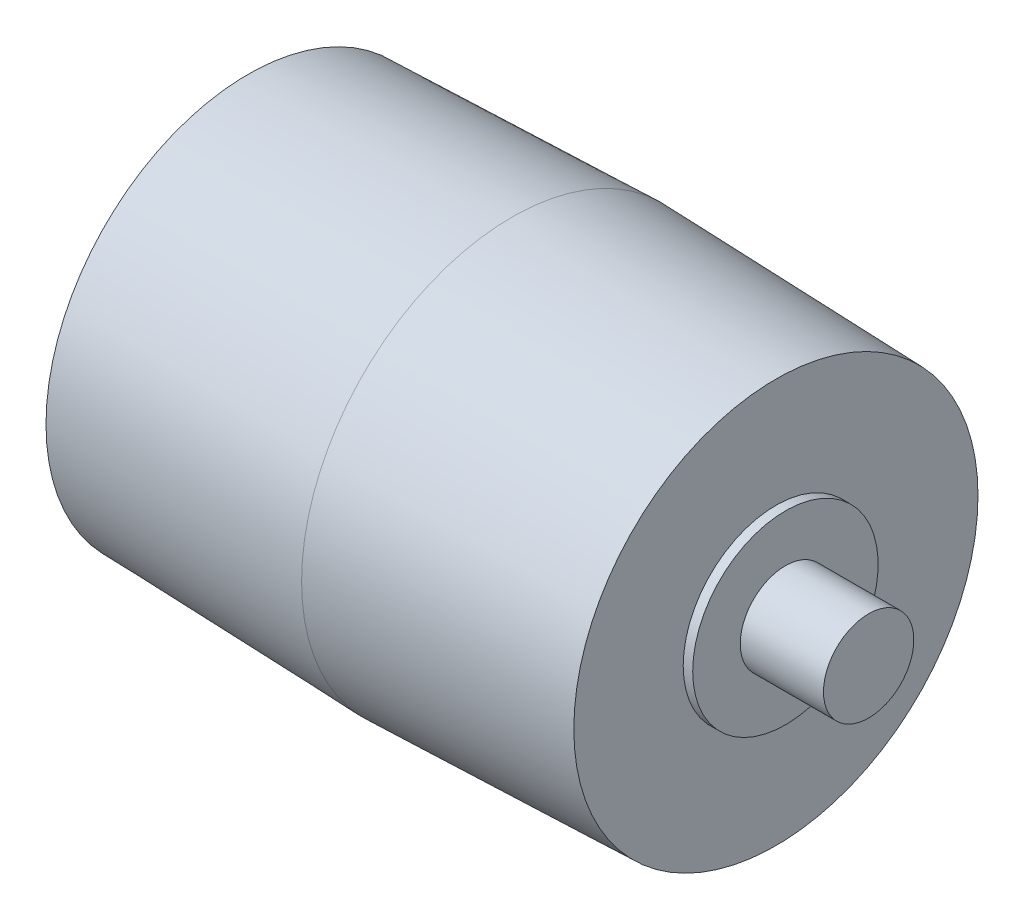
SolidWorks part; units mm, degrees
ref_plane "Front Plane" through (0, 0, 0) normal (0, 0, 1) x (1, 0, 0)
ref_plane "Top Plane" through (0, 0, 0) normal (0, 1, 0) x (1, 0, 0)
ref_plane "Right Plane" through (0, 0, 0) normal (1, 0, 0) x (0, 0, -1)
sketch "Sketch1" plane through (0, 0, 0) normal (0, 0, 1) x (1, 0, 0)
  line L0 (-9.525, 0) -> (-9.525, 1.2065)
  line L1 (-9.525, 1.2065) -> (-7.3025, 1.2065)
  line L2 (-7.3025, 1.2065) -> (-7.3025, 2.4765)
  line L3 (-7.3025, 2.4765) -> (-7.0485, 2.4765)
  line L4 (-7.0485, 2.4765) -> (-7.0485, 5.3975)
  line L5 (-7.0485, 5.3975) -> (0, 5.6197)
  line L6 (0, 5.6197) -> (0, 0) construction
  line L7 (9.525, 0) -> (-9.525, 0) construction
  line L8 (7.0485, 5.3975) -> (0, 5.6197)
  line L9 (7.0485, 2.4765) -> (7.0485, 5.3975)
  line L10 (7.3025, 2.4765) -> (7.0485, 2.4765)
  line L11 (7.3025, 1.2065) -> (7.3025, 2.4765)
  line L12 (9.525, 1.2065) -> (7.3025, 1.2065)
  line L13 (9.525, 0) -> (9.525, 1.2065)
  line L14 (-9.525, 0) -> (9.525, 0)
  dimension "D1" = 19.05
  dimension "D2" = 2.413
  dimension "D3" = 14.605
  dimension "D4" = 14.097
  dimension "D5" = 11.2395
  dimension "D6" = 10.795
  dimension "D7" = 4.953
revolve "Revolve1" add sketch "Sketch1" angle 360 about L14
